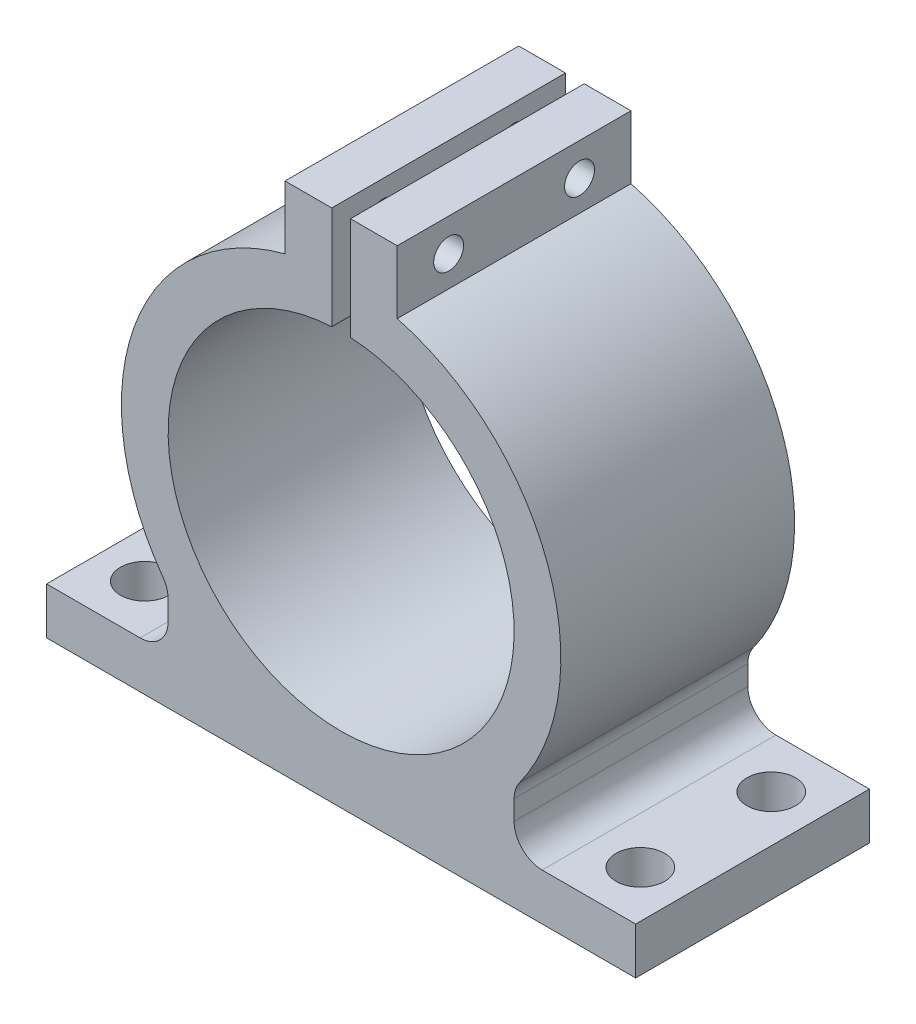
SolidWorks part; units mm, degrees
ref_plane "Front Plane" through (0, 0, 0) normal (0, 0, 1) x (1, 0, 0)
ref_plane "Top Plane" through (0, 0, 0) normal (0, 1, 0) x (1, 0, 0)
ref_plane "Right Plane" through (0, 0, 0) normal (1, 0, 0) x (0, 0, -1)
sketch "Sketch1" plane through (0, 0, 0) normal (0, 0, 1) x (1, 0, 0)
  line L0 (-18.473, -1) -> (18.473, -1) construction
  line L3 (0, -1) -> (0, -25.6) construction
  line L4 (-18.5, -25.6) -> (18.5, -25.6)
  line L5 (-18.5, -25.6) -> (-18.5, -14.4914)
  line L6 (18.5, -25.6) -> (18.5, -14.4914)
  line L14 (-1, 18.473) -> (-1, 29.473)
  line L15 (1, 18.473) -> (1, 29.473)
  line L16 (1, 29.473) -> (6, 29.473)
  line L17 (6, 29.473) -> (6, 22.7211)
  line L18 (-1, 29.473) -> (-6, 29.473)
  line L19 (-6, 29.473) -> (-6, 22.7211)
  circle A0 centre (0, 0) radius 18.5 construction
  arc A4 (-18.5, -14.4914) -> (-6, 22.7211) centre (0, 0) cw
  arc A5 (18.5, -14.4914) -> (6, 22.7211) centre (0, 0) ccw
  arc A7 (1, 18.473) -> (-1, 18.473) centre (0, 0) cw
  point P11 (0, -7.1)
  dimension "D1" = 37
  dimension "D3" = 37
  dimension "D4" = 2
  dimension "D8" = 23.5
  dimension "D9" = 23.5
  dimension "D2" = 1
  dimension "D5" = 18.5
  dimension "D6" = 7.1
  dimension "D7" = 5
  dimension "D10" = 5
  dimension "D11" = 11
extrude "Boss-Extrude1" add sketch "Sketch1" along normal blind 25
sketch "Sketch2" plane through (-18.5, 0, 0) normal (-1, 0, 0) x (0, 0, 1)
  line L0 (25, -25.6) -> (0, -25.6) construction
  line L1 (25, -20.6) -> (0, -20.6)
  line L2 (25, -20.6) -> (25, -25.6)
  line L3 (25, -25.6) -> (0, -25.6)
  line L4 (0, -20.6) -> (0, -25.6)
  line L5 (0, -14.4914) -> (0, -25.6) construction
  line L6 (25, -14.4914) -> (25, -25.6) construction
  dimension "D1" = 5
extrude "Boss-Extrude2" add sketch "Sketch2" along normal blind 13
fillet "Fillet1" radius 3 2 edges at (-18.5, -14.4914, 12.5) (-18.5, -20.6, 12.5)
sketch "Sketch3" plane through (0, -20.6, 0) normal (0, 1, 0) x (1, 0, 0)
  line L0 (-26.5, -5.5) -> (-26.5, -19.5) construction
  line L1 (-31.5, -12.5) -> (-21.5, -12.5) construction
  line L2 (-31.5, -25) -> (-31.5, 0) construction
  line L3 (-21.5, -25) -> (-21.5, 0) construction
  circle A0 centre (-26.5, -19.5) radius 2.6
  circle A1 centre (-26.5, -5.5) radius 2.6
  point P10 (-26.5, -12.5)
  point P13 (-26.5, -12.5)
  dimension "D1" = 5.2
  dimension "D2" = 5.2
  dimension "D3" = 14
extrude "Cut-Extrude1" cut sketch "Sketch3" against normal through all
mirror "Mirror3" about plane through (0, 0, 0) normal (1, 0, 0) of "Boss-Extrude2", "Cut-Extrude1"
fillet "Fillet2" radius 3 2 edges at (18.5, -14.4914, 12.5) (18.5, -20.6, 12.5)
sketch "Sketch4" plane through (-6, 0, 0) normal (-1, 0, 0) x (0, 0, 1)
  line L0 (12.5, 29.473) -> (12.5, 22.7211) construction
  line L7 (25, 29.473) -> (0, 29.473) construction
  line L8 (5.5, 25.973) -> (19.5, 25.973) construction
  line L9 (25, 22.7211) -> (0, 22.7211) construction
  circle A0 centre (19.5, 25.973) radius 1.6
  circle A1 centre (5.5, 25.973) radius 1.6
  point P6 (0, 0)
  point P8 (12.5, 25.973)
  dimension "D1" = 3.5
  dimension "D2" = 3.2
  dimension "D3" = 3.2
  dimension "D4" = 14
extrude "Cut-Extrude2" cut sketch "Sketch4" against normal through all
